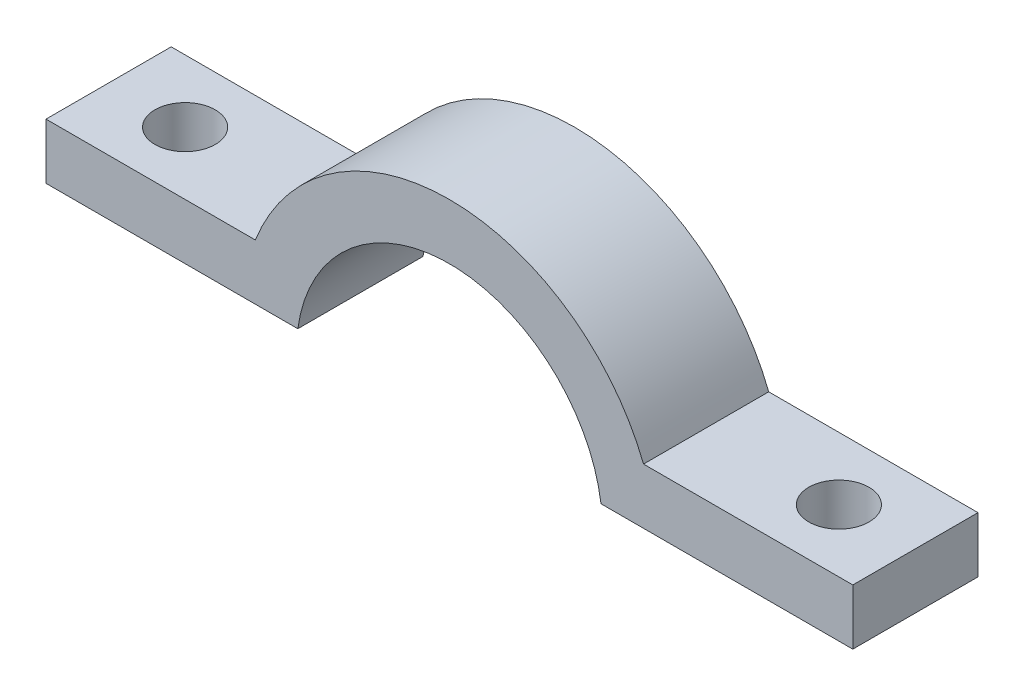
SolidWorks part; units mm, degrees
ref_plane "Front Plane" through (0, 0, 0) normal (0, 0, 1) x (1, 0, 0)
ref_plane "Top Plane" through (0, 0, 0) normal (0, 1, 0) x (1, 0, 0)
ref_plane "Right Plane" through (0, 0, 0) normal (1, 0, 0) x (0, 0, -1)
sketch "Sketch1" plane through (0, 0, 0) normal (0, 0, 1) x (1, 0, 0)
  line L0 (18.0566, -9.075) -> (-0.8028, 0.4035) construction
  line L2 (29, -13.075) -> (29, -9.075)
  line L4 (-29, -13.075) -> (-29, -9.075)
  line L5 (26.0154, -13.075) -> (24.2978, -12.2117) construction
  line L10 (-29, -13.075) -> (-10.8972, -13.075)
  line L11 (29, -13.075) -> (10.8972, -13.075)
  line L12 (-29, -9.075) -> (-13.9553, -9.075)
  line L13 (13.9553, -9.075) -> (29, -9.075)
  line L15 (-23.5, -11.8108) -> (-29, -14.575) construction
  line L18 (0.8028, 0.4035) -> (-18.0566, -9.075) construction
  arc A0 (10.8972, -13.075) -> (-10.8972, -13.075) centre (0, -14.575) ccw
  arc A1 (13.9553, -9.075) -> (-13.9553, -9.075) centre (0, -14.575) ccw
  point P1 (0, 0)
  dimension "D4" = 22
  dimension "D6" = 30
  dimension "D7" = 4
extrude "Boss-Extrude1" add sketch "Sketch1" along normal blind 9
sketch "Sketch2" plane through (0, -9.075, 0) normal (0, 1, 0) x (1, 0, 0)
  line L0 (-23.5, -4.5) -> (23.5, -4.5) construction
  line L1 (-29, -9) -> (-29, 0) construction
  line L2 (-23.5, -4.5) -> (-29, -4.5) construction
  line L3 (23.5, -4.5) -> (29, -4.5) construction
  line L4 (29, -9) -> (29, 0) construction
  line L5 (-23.5, 0) -> (-23.5, -4.5) construction
  line L6 (-13.9553, 0) -> (-29, 0) construction
  line L7 (-23.5, -4.5) -> (-23.5, -9) construction
  line L8 (-13.9553, -9) -> (-29, -9) construction
  circle A0 centre (-23.5, -4.5) radius 2.165
  circle A1 centre (23.5, -4.5) radius 2.165
  dimension "D1" = 47
extrude "Cut-Extrude1" cut sketch "Sketch2" against normal through all
